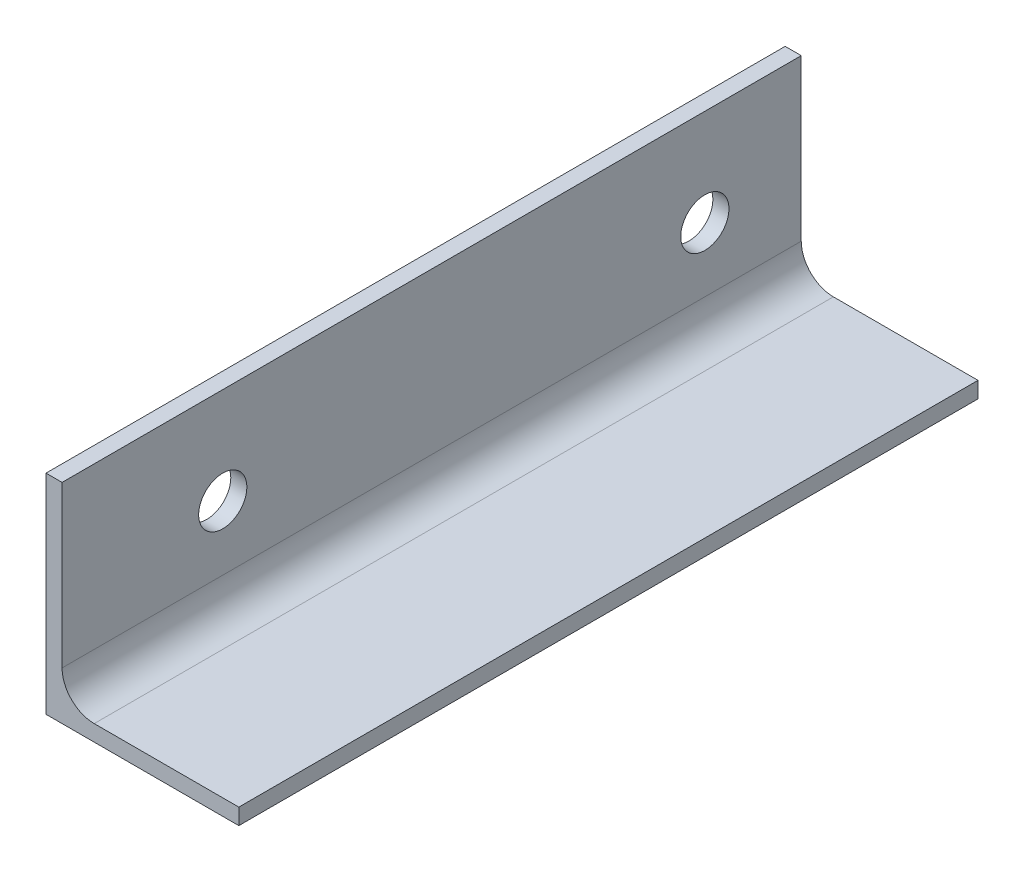
SolidWorks part; units mm, degrees
ref_plane "Front Plane" through (0, 0, 0) normal (0, 0, 1) x (1, 0, 0)
ref_plane "Top Plane" through (0, 0, 0) normal (0, 1, 0) x (1, 0, 0)
ref_plane "Right Plane" through (0, 0, 0) normal (1, 0, 0) x (0, 0, -1)
sketch "Sketch1" plane through (0, 0, 0) normal (0, 0, 1) x (1, 0, 0)
  line L2 (2.5, -20) -> (2.5, 30)
  line L3 (2.5, 30) -> (-2.5, 30)
  line L4 (-2.5, -30) -> (-2.5, 30)
  line L5 (2.5, -30) -> (-2.5, 30) construction
  line L6 (2.5, 30) -> (-2.5, -30) construction
  line L7 (12.5, -30) -> (57.5, -30)
  line L8 (-2.5, -30) -> (-2.5, -35)
  line L9 (-2.5, -35) -> (57.5, -35)
  line L10 (57.5, -30) -> (57.5, -35)
  arc A0 (12.5, -30) -> (2.5, -20) centre (12.5, -20) cw
  point P0 (0, 0)
  dimension "D6" = 10
  dimension "D1" = 5
  dimension "D2" = 60
  dimension "D3" = 5
  dimension "D4" = 60
  dimension "D5" = 60
extrude "Boss-Extrude1" add sketch "Sketch1" along normal blind 230
sketch "Sketch2" plane through (2.5, 0, 0) normal (1, 0, 0) x (0, 0, -1)
  line L0 (-230, 30) -> (0, 30) construction
  line L1 (0, -20) -> (0, 30) construction
  circle A0 centre (-30, 0) radius 7.5
  circle A1 centre (-180, 0) radius 7.5
  point P8 (0, 0)
  dimension "D3" = 15
  dimension "D4" = 15
  dimension "D1" = 30
  dimension "D2" = 30
  dimension "D5" = 150
  dimension "D6" = 30
extrude "Cut-Extrude1" cut sketch "Sketch2" against normal up to next
